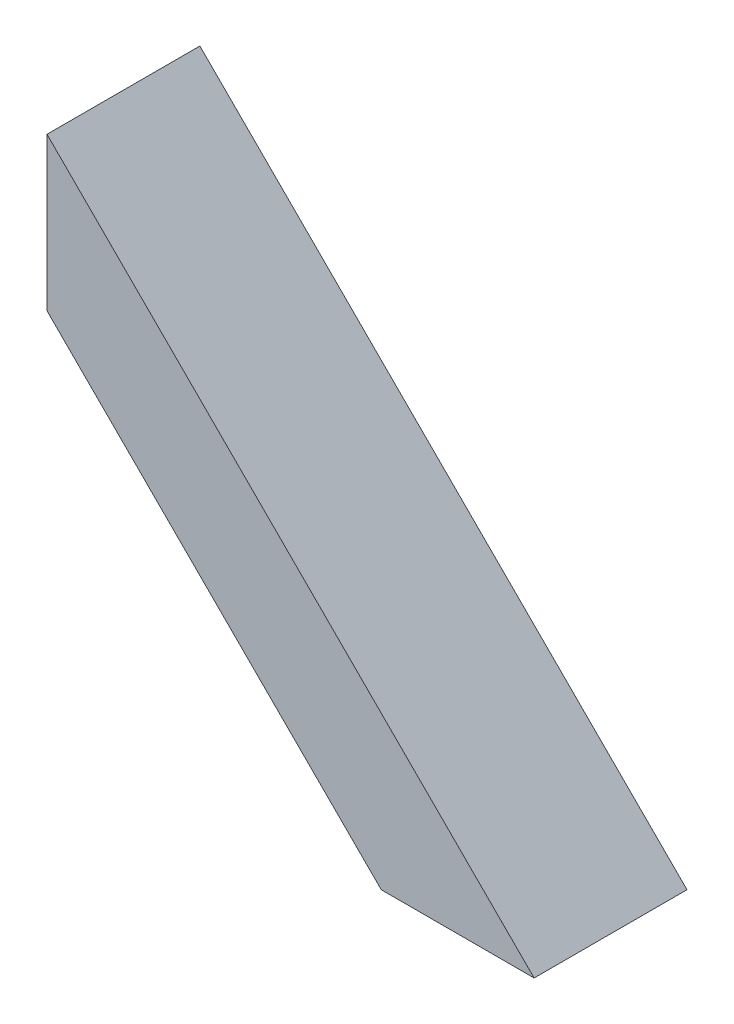
SolidWorks part; units mm, degrees
ref_plane "Front Plane" through (0, 0, 0) normal (0, 0, 1) x (1, 0, 0)
ref_plane "Top Plane" through (0, 0, 0) normal (0, 1, 0) x (1, 0, 0)
ref_plane "Right Plane" through (0, 0, 0) normal (1, 0, 0) x (0, 0, -1)
sketch "Sketch1" plane through (0, 0, 0) normal (0, 0, 1) x (1, 0, 0)
  line L0 (-7.1911, 5.0481) -> (-7.1911, 0.0481)
  line L1 (-7.1911, 0.0481) -> (3.7411, -10.8842)
  line L2 (3.7411, -10.8842) -> (8.7411, -10.8842)
  line L3 (8.7411, -10.8842) -> (-7.1911, 5.0481)
  dimension "D1" = 5
  dimension "D2" = 5
  dimension "D3" = 22.5316
extrude "Boss-Extrude1" add sketch "Sketch1" along normal blind 5
